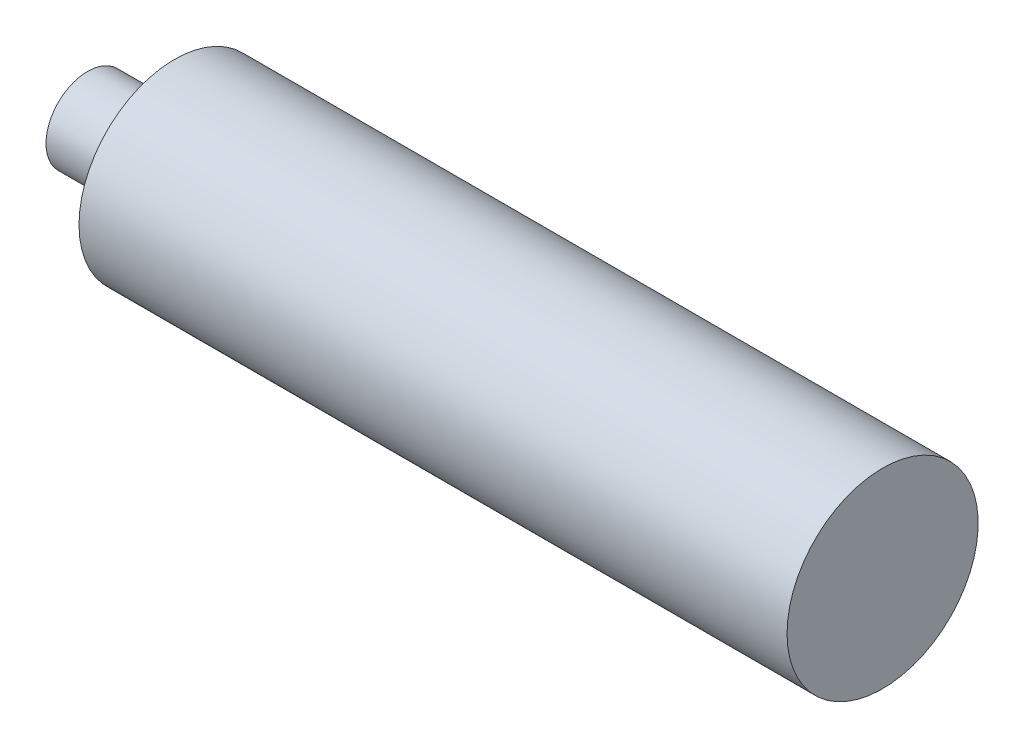
SolidWorks part; units mm, degrees
ref_plane "Front Plane" through (0, 0, 0) normal (0, 0, 1) x (1, 0, 0)
ref_plane "Top Plane" through (0, 0, 0) normal (0, 1, 0) x (1, 0, 0)
ref_plane "Right Plane" through (0, 0, 0) normal (1, 0, 0) x (0, 0, -1)
sketch "Sketch1" plane through (-304.8, 0, 0) normal (-1, 0, 0) x (0, 0, 1)
  circle A0 centre (-139.7, 32.815) radius 11
  circle A1 centre (-139.7, 50.165) radius 6.35
  circle A2 centre (-139.7, 50.165) radius 6.35 construction
  dimension "D2" = 22
  dimension "D1" = 0
extrude "Boss-Extrude1" add sketch "Sketch1" against normal blind 81.5
sketch "Sketch2" plane through (-304.8, 0, 0) normal (-1, 0, 0) x (0, 0, 1)
  circle A0 centre (-139.7, 32.815) radius 4.8
  dimension "D1" = 9.6
extrude "Boss-Extrude2" add sketch "Sketch2" along normal blind 10
